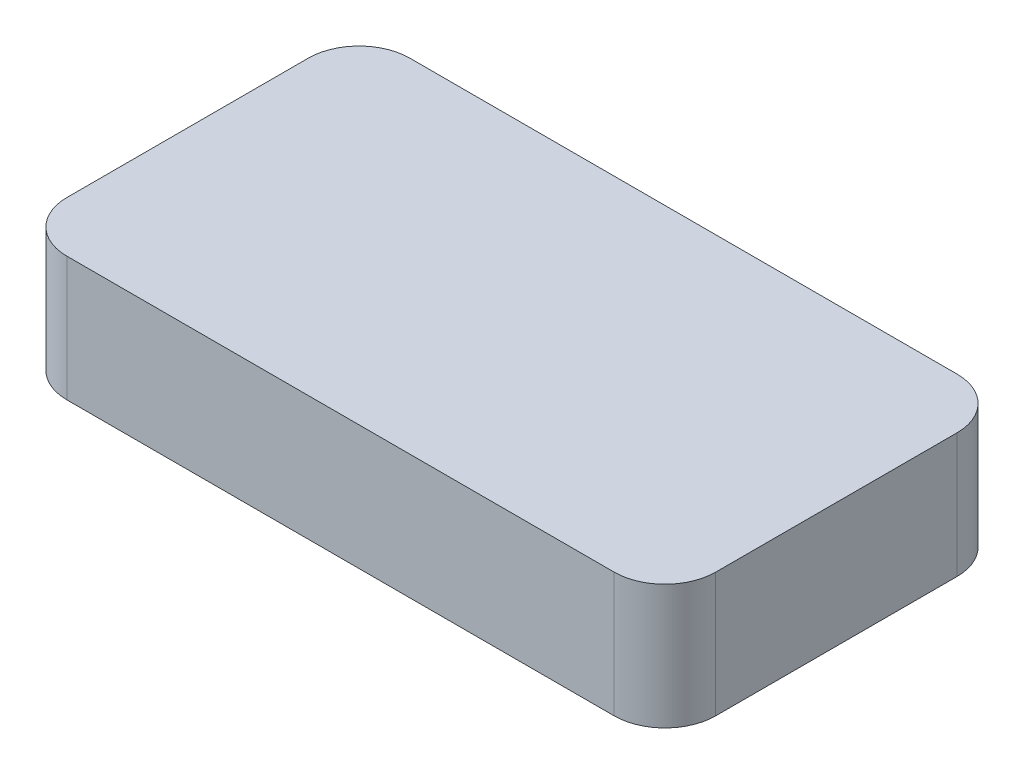
SolidWorks part; units mm, degrees
ref_plane "Front Plane" through (0, 0, 0) normal (0, 0, 1) x (1, 0, 0)
ref_plane "Top Plane" through (0, 0, 0) normal (0, 1, 0) x (1, 0, 0)
ref_plane "Right Plane" through (0, 0, 0) normal (1, 0, 0) x (0, 0, -1)
sketch "Sketch1" plane through (0, 0, 0) normal (0, 1, 0) x (1, 0, 0)
  line L1 (0, 0) -> (32.4358, 0)
  line L2 (0, 0) -> (0, 17.145)
  line L3 (0, 17.145) -> (32.4358, 17.145)
  line L4 (32.4358, 0) -> (32.4358, 17.145)
  dimension "D1" = 32.4358
  dimension "D2" = 17.145
extrude "Boss-Extrude1" add sketch "Sketch1" along normal blind 6.223
fillet "Fillet1" radius 2.54 4 edges at (32.4358, 3.1115, -17.145) (32.4358, 3.1115, 0) (0, 3.1115, 0) (0, 3.1115, -17.145)
